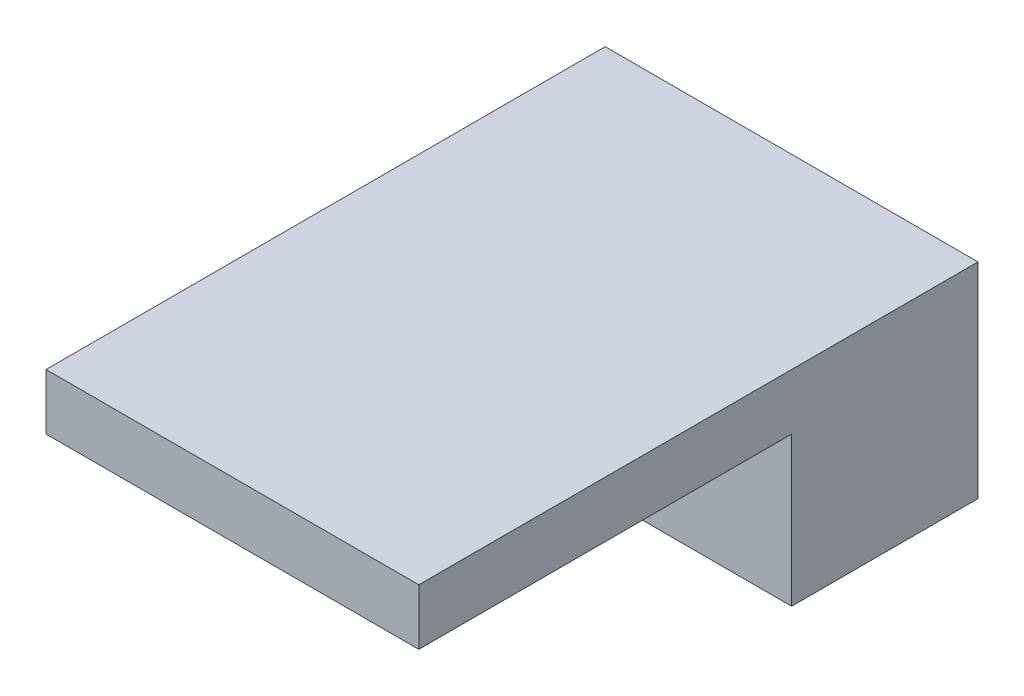
SolidWorks part; units mm, degrees
material "ABS"
ref_plane "前视基准面" through (0, 0, 0) normal (0, 0, 1) x (1, 0, 0)
ref_plane "上视基准面" through (0, 0, 0) normal (0, 1, 0) x (1, 0, 0)
ref_plane "右视基准面" through (0, 0, 0) normal (1, 0, 0) x (0, 0, -1)
sketch "草图1" plane through (0, 0, 0) normal (0, 1, 0) x (1, 0, 0)
  line L0 (0, -20) -> (20, -20)
  line L1 (0, 0) -> (20, 0)
  line L2 (0, 0) -> (0, -30)
  line L3 (0, -30) -> (20, -30)
  line L4 (20, 0) -> (20, -30)
  dimension "D1" = 30
  dimension "D2" = 20
  dimension "D3" = 10
extrude "凸台-拉伸1" add sketch "草图1" along normal blind 3 contours L4 L3 L2 L1
sketch "草图4" plane through (0, 0, 0) normal (0, -1, 0) x (1, 0, 0)
  line L0 (0, 10) -> (20, 10)
  line L1 (0, 0) -> (0, 30) construction
  line L2 (20, 0) -> (20, 30) construction
  line L3 (0, 0) -> (20, 0) construction
  line L8 (0, 0) -> (20, 0)
  line L9 (20, 0) -> (20, 30)
  line L10 (20, 30) -> (0, 30)
  line L11 (0, 30) -> (0, 0)
  line L12 (0, 0) -> (20, 0)
  line L13 (20, 0) -> (20, 10)
  line L15 (0, 10) -> (0, 0)
  dimension "D1" = 10
  dimension "D2" = 0
extrude "凸台-拉伸2" add sketch "草图4" along normal blind 8
